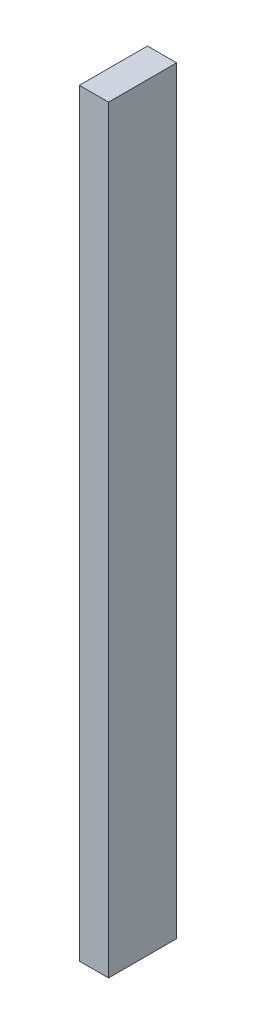
SolidWorks part; units mm, degrees
material "Pine"
ref_plane "Front Plane" through (0, 0, 0) normal (0, 0, 1) x (1, 0, 0)
ref_plane "Top Plane" through (0, 0, 0) normal (0, 1, 0) x (1, 0, 0)
ref_plane "Right Plane" through (0, 0, 0) normal (1, 0, 0) x (0, 0, -1)
sketch "Sketch1" plane through (0, 0, 0) normal (0, 1, 0) x (1, 0, 0)
  line L1 (-19.05, -44.45) -> (19.05, -44.45)
  line L2 (-19.05, -44.45) -> (-19.05, 44.45)
  line L3 (-19.05, 44.45) -> (19.05, 44.45)
  line L4 (19.05, -44.45) -> (19.05, 44.45)
  line L5 (-19.05, -44.45) -> (19.05, 44.45) construction
  line L6 (-19.05, 44.45) -> (19.05, -44.45) construction
  point P0 (0, 0)
  dimension "D1" = 88.9
  dimension "D2" = 38.1
extrude "Boss-Extrude1" add sketch "Sketch1" along normal mid plane 990.6
hole_wizard "1/2 Clearance Hole1" positions "Sketch2" profile "Sketch3" hole size "1/2" standard "ANSI Inch"
sketch "Sketch2" plane through (-44.45, 0, 0) normal (-1, 0, 0) x (0, 0, 1)
  line L0 (0, 495.3) -> (0, -489.3469) construction
  line L1 (-44.45, 495.3) -> (44.45, 495.3) construction
  line L2 (-44.45, -495.3) -> (44.45, -495.3) construction
  point P6 (0, -342.9)
  point P10 (0, 342.9)
  dimension "D1" = 152.4
  dimension "D2" = 152.4
sketch "Sketch3" plane through (-44.45, 342.9, 0) normal (0, 1, 0) x (0, 0, 1)
  line L0 (0, 0) -> (0, 88.9)
  line L1 (0, 88.9) -> (6.7462, 88.9)
  line L2 (6.7462, 88.9) -> (6.7462, 0)
  line L5 (6.7462, 0) -> (0, 0)
  line L11 (0, -6.35) -> (0, 107.95) construction
  dimension "Thru Hole Dia." = 13.4925
  dimension "Thru Hole Depth" = 88.9
hole_wizard "23/64 (0.35938) Diameter Hole1" positions "Sketch4" profile "Sketch5" hole size "23/64" standard "ANSI Inch"
sketch "Sketch4" plane through (-19.05, 0, 0) normal (-1, 0, 0) x (0, 0, 1)
  line L0 (0, 495.3) -> (0, -495.3) construction
  line L1 (-44.45, 495.3) -> (44.45, 495.3) construction
  line L2 (-44.45, -495.3) -> (44.45, -495.3) construction
  line L4 (-44.45, 190.5) -> (44.45, 190.5) construction
  line L5 (-44.45, 495.3) -> (-44.45, -495.3) construction
  line L6 (44.45, 495.3) -> (44.45, -495.3) construction
  line L8 (-19.05, 495.3) -> (-19.05, -495.3) construction
  line L9 (-44.45, 234.95) -> (44.45, 234.95) construction
  point P21 (0, 215.9)
  point P23 (0, 165.1)
  dimension "D1" = 304.8
  dimension "D2" = 25.4
  dimension "D3" = 44.45
  dimension "D4" = 19.05
sketch "Sketch5" plane through (-19.05, 165.1, 0) normal (0, 1, 0) x (0, 0, 1)
  line L0 (0, 0) -> (0, 38.1)
  line L1 (0, 38.1) -> (4.5641, 38.1)
  line L2 (4.5641, 38.1) -> (4.5641, 0)
  line L5 (4.5641, 0) -> (0, 0)
  line L11 (0, -6.35) -> (0, 107.95) construction
  dimension "Thru Hole Dia." = 9.1283
  dimension "Thru Hole Depth" = 38.1
